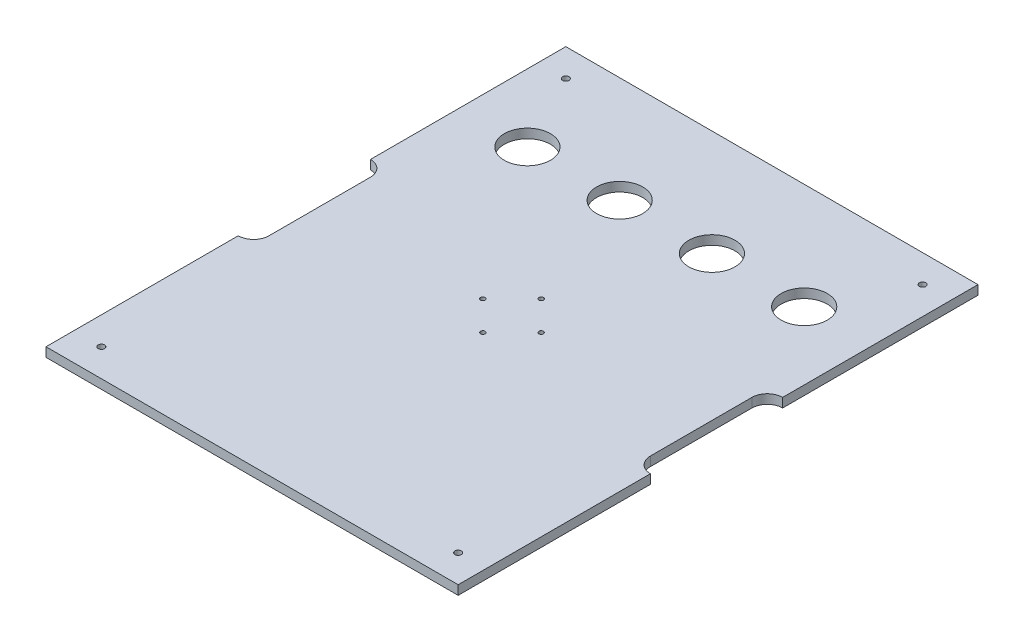
SolidWorks part; units mm, degrees
material "Acrílico (médio-alto impacto)"
ref_plane "Plano frontal" through (0, 0, 0) normal (0, 0, 1) x (1, 0, 0)
ref_plane "Plano superior" through (0, 0, 0) normal (0, 1, 0) x (1, 0, 0)
ref_plane "Plano direito" through (0, 0, 0) normal (1, 0, 0) x (0, 0, -1)
sketch "Esboço1" plane through (0, 0, 0) normal (0, 1, 0) x (1, 0, 0)
  line L1 (-134, -169) -> (134, -169)
  line L2 (-134, -169) -> (-134, -44)
  line L3 (-134, 169) -> (134, 169)
  line L4 (134, -169) -> (134, -44)
  line L5 (-134, -169) -> (134, 169) construction
  line L6 (-134, 169) -> (134, -169) construction
  line L7 (124, -34) -> (124, 32)
  line L9 (134, 42) -> (134, 169)
  line L11 (-124, -34) -> (-124, 32)
  line L12 (-134, 42) -> (-134, 169)
  arc A0 (124, -34) -> (134, -44) centre (134, -34) ccw
  arc A1 (134, 42) -> (124, 32) centre (134, 32) ccw
  arc A2 (-134, -44) -> (-124, -34) centre (-134, -34) ccw
  arc A3 (-124, 32) -> (-134, 42) centre (-134, 32) ccw
  point P0 (0, 0)
  point P8 (124, -1)
  dimension "D3" = 10
  dimension "D4" = 10
  dimension "D1" = 338
  dimension "D2" = 268
  dimension "D5" = 66
  dimension "D6" = 66
  dimension "D7" = 170
extrude "Ressalto-extrusão1" add sketch "Esboço1" along normal blind 6
hole_wizard "Furo roscado de M41" positions "Esboço3" profile "Esboço5" tap size "M4" standard "ISO" end condition through all
sketch "Esboço3" plane through (0, 0, 0) normal (0, -1, 0) x (-1, 0, 0)
  line L1 (0, 79.1495) -> (0, -66.999) construction
  line L4 (-134, 0) -> (96, 0) construction
  line L5 (-134, -175) -> (-134, 175) construction
  point P44 (0, 19)
  point P46 (-19, 0)
  point P50 (0, -19)
  point P63 (19, 0)
  dimension "D1" = 19
  dimension "D2" = 38
  dimension "D4" = 19
  dimension "D5" = 38
sketch "Esboço5" plane through (-19, 0, 0) normal (1, 0, 0) x (0, 0, -1)
  line L0 (0, 0) -> (0, 6)
  line L1 (0, 6) -> (1.5, 6)
  line L2 (1.5, 6) -> (1.5, 0)
  line L5 (1.5, 0) -> (0, 0)
  line L11 (0, -6.35) -> (0, 107.95) construction
  dimension "Thru Tap Drill Dia." = 3
  dimension "Thru Tap Drill Depth" = 6
sketch "Esboço6" plane through (0, 6, 0) normal (0, 1, 0) x (1, 0, 0)
  circle A0 centre (-90, 100) radius 15
  circle A1 centre (-30, 100) radius 15
  circle A2 centre (30, 100) radius 15
  circle A3 centre (90, 100) radius 15
  dimension "D1" = 30
  dimension "D4" = 30
  dimension "D2" = 100
  dimension "D3" = 60
  dimension "D5" = 60
  dimension "D6" = 60
extrude "Corte-extrusão1" cut sketch "Esboço6" against normal through all
hole_wizard "Furo de diâmetro Ø4.2 (4.2)1" positions "Esboço13" profile "Esboço14" hole size "Ø4.2" standard "ISO" end condition through all
sketch "Esboço13" plane through (0, 0, 0) normal (0, -1, 0) x (-1, 0, 0)
  point P0 (-116, 151)
  point P9 (-116, -151)
  point P16 (116, 151)
  point P19 (116, -151)
sketch "Esboço14" plane through (116, 0, -151) normal (1, 0, 0) x (0, 0, -1)
  line L0 (0, 0) -> (0, 6)
  line L1 (0, 6) -> (2.1, 6)
  line L2 (2.1, 6) -> (2.1, 0)
  line L5 (2.1, 0) -> (0, 0)
  line L11 (0, -6.35) -> (0, 107.95) construction
  dimension "Thru Hole Dia." = 4.2
  dimension "Thru Hole Depth" = 6
